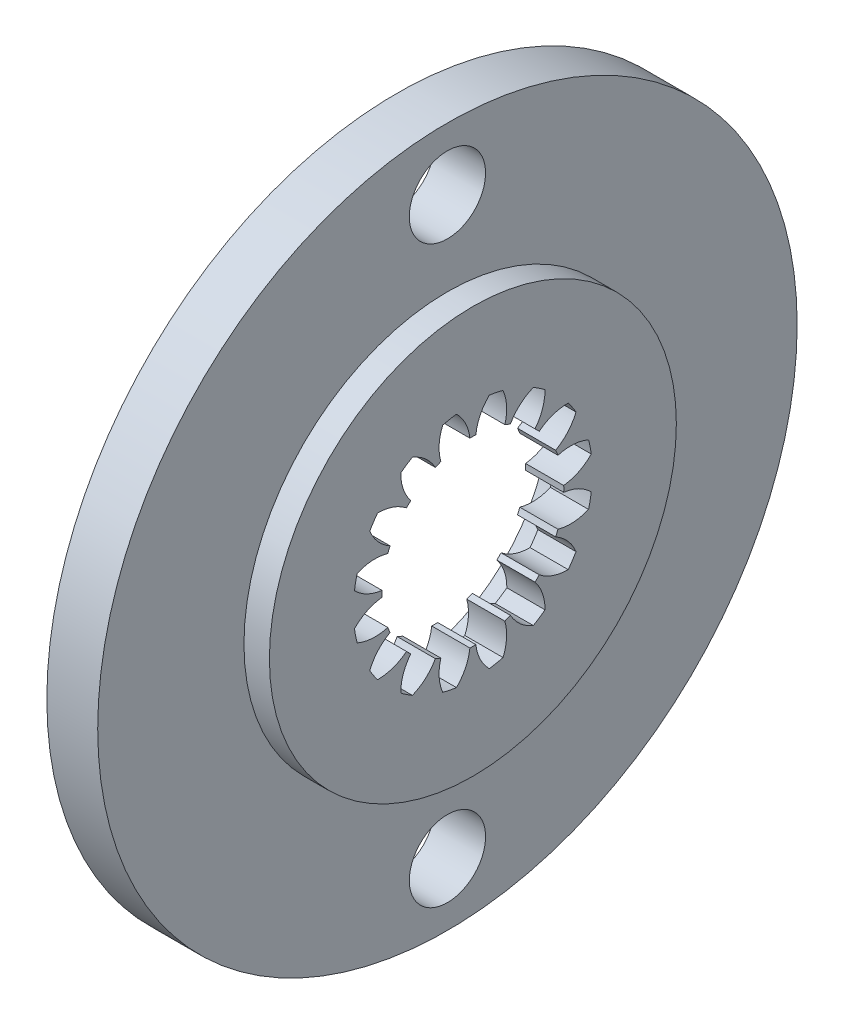
SolidWorks part; units mm, degrees
ref_plane "Plane1" through (0, 0, 0) normal (0, 0, 1) x (1, 0, 0)
ref_plane "Plane2" through (0, 0, 0) normal (0, 1, 0) x (1, 0, 0)
ref_plane "Plane3" through (0, 0, 0) normal (1, 0, 0) x (0, 0, -1)
sketch "HoldingSke" plane through (0, 0, 0) normal (0, 1, 0) x (1, 0, 0)
  line L0 (0, 0) -> (1.9225, -0.5513)
  line L1 (-15, 0) -> (100, 0) construction
  line L2 (0, 0) -> (-2.1039, 2.3779)
  line L3 (0, 0) -> (-11.863, 4.5341)
  line L4 (0, 0) -> (8.3015, 2.3804)
  line L5 (0, 0) -> (-46.8476, -17.4728)
  line L6 (0, 0) -> (-6.2172, -4.1948)
  line L7 (-2.1039, 2.3779) -> (8.6586, 51.2059)
  line L8 (-76.2, 54.61) -> (-75.3, 54.61)
  line L9 (-67.7845, 28.3722) -> (-49.3413, 33.142)
  line L10 (-76.2, 71.12) -> (104.1128, 71.12)
  line L11 (0, 0) -> (-7.5, 0)
  line L12 (-76.2, 101.6) -> (-76.181, 101.6)
  line L13 (24.9733, 27.94) -> (52.9518, 28.4284)
  line L14 (24.9733, 27.94) -> (24.9743, 27.94)
  line L15 (24.9733, 27.94) -> (100.4006, 29.5858)
  line L16 (-63.627, -0.5) -> (-12.827, -0.5)
  circle A0 centre (0, 0) radius 2.5
  circle A1 centre (0, 0) radius 3.374
  circle A2 centre (0, 0) radius 37.5
  circle A3 centre (0, 0) radius 2.5
  dimension "MHD" = 6.748
  dimension "Hub_dia" = 75
  dimension "Bore" = 5
  dimension "MBD" = 5
  dimension "Num_teeth" = 16
  dimension "Pitch" = 2
  dimension "Overall_len" = 50
  dimension "Show_teeth" = 16
  dimension "Thickness" = 7.5
  dimension "OAL" = 50.0001
  dimension "T_dim" = 0.9
  dimension "Ap" = 14.5
  dimension "H" = 19.05
  dimension "Pitch_radius" = 180.3128
  dimension "Width" = 7.5
  dimension "Backlash" = 0.019
  dimension "Addendum_fac" = 1
  dimension "Dedendum_fac" = 1.25
  dimension "Clearance_fac" = 0.25
  dimension "Dedendum_add" = 0.001
  dimension "Module" = 0.5
sketch "BasProSke" plane through (0, 0, 0) normal (0, 1, 0) x (1, 0, 0)
  line L0 (-10, 0) -> (60, 0) construction
  line L1 (0, 0) -> (0, 4.5)
  line L2 (0, 0) -> (7.5, 0)
  line L3 (7.5, 0) -> (7.5, 4.5)
  line L4 (7.5, 4.5) -> (0, 4.5)
  dimension "Thickness" = 7.5
  dimension "Diameter" = 9
revolve "Base-Revolve" add sketch "BasProSke" angle 360 about L0
sketch "TooCutSke" plane through (0, 0, 0) normal (1, 0, 0) x (0, 0, -1)
  line L1 (0, 0) -> (0, 107) construction
  line L2 (0, 0) -> (-0.4253, 3.9773) construction
  line L3 (0, 0) -> (-1.5544, 7.8146) construction
  line L4 (-0.4253, 3.9773) -> (-0.7772, 3.9073) construction
  arc A0 (0.306, 3.3601) -> (-0.306, 3.3601) centre (0, 0) ccw
  arc A1 (0.7382, 4.4648) -> (-0.7382, 4.4648) centre (0, 0) ccw
  circle A2 centre (0, 0) radius 4 construction
  circle A3 centre (0, 0) radius 3.8726 construction
  arc A4 (-0.306, 3.3601) -> (-0.7382, 4.4648) centre (-1.906, 3.3711) ccw
  arc A5 (0.7382, 4.4648) -> (0.306, 3.3601) centre (1.906, 3.3711) ccw
  dimension "Root_dia" = 6.748
  dimension "Overcut_dia" = 9.0508
  dimension "Pitch_dia" = 8
  dimension "Base_dia" = 7.7452
  dimension "Flank_rad" = 1.6
  dimension "Half_ang" = 11.25
  dimension "Half_CT" = 0.3588
extrude "ToothCut" cut sketch "TooCutSke" along normal through all
fillet "Breaks" [suppressed] radius 0.01
fillet "RootFillets" [suppressed] radius 0.126
pattern_circular "TeethCuts" count 16 every 22.5 about axis through (-10, 0, 0) along (1, 0, 0) of "ToothCut", "RootFillets", "Breaks"
sketch "HubNeaOneSke" plane through (0, 0, 0) normal (-1, 0, 0) x (0, 0, 1)
  circle A0 centre (0, 0) radius 3.374
  dimension "Diameter" = 6.748
extrude "HubNearOne" [suppressed] add sketch "HubNeaOneSke" along normal blind 42.5001
sketch "HubNeaBotSke" plane through (0, 0, 0) normal (-1, 0, 0) x (0, 0, 1)
  circle A0 centre (0, 0) radius 3.374
  dimension "Diameter" = 6.748
extrude "HubNearBoth" [suppressed] add sketch "HubNeaBotSke" along normal blind 21.25
ref_plane "FarPln" through (7.5, 0, 0) normal (1, 0, 0) x (0, 0, -1)
sketch "HubFarSke" plane through (7.5, 0, 0) normal (1, 0, 0) x (0, 0, -1)
  circle A0 centre (0, 0) radius 3.374
  dimension "Diameter" = 6.748
extrude "HubFar" [suppressed] add sketch "HubFarSke" along normal blind 21.25
sketch "BorSke" plane through (0, 0, 0) normal (1, 0, 0) x (0, 0, -1)
  circle A0 centre (0, 0) radius 2.5
  dimension "Diameter" = 5
extrude "Bore" cut sketch "BorSke" along normal mid plane 100.0001
sketch "KeySke" plane through (0, 0, 0) normal (1, 0, 0) x (0, 0, -1)
  line L0 (-1, 0) -> (-1, 3.4)
  line L1 (-1, 3.4) -> (1, 3.4)
  line L2 (1, 3.4) -> (1, 0)
  line L3 (0, 0) -> (0, 34) construction
  line L4 (-1, 0) -> (1, 0)
  dimension "Offset" = 3.4
  dimension "Width" = 2
extrude "Keyway" [suppressed] cut sketch "KeySke" along normal mid plane 100.0001
pattern_circular "Keyway2" [suppressed] count 2 every 90 about axis through (-10, 0, 0) along (1, 0, 0)
sketch "Esquisse4" plane through (0, 0, 0) normal (-1, 0, 0) x (0, 0, 1)
  circle A1 centre (0, 0) radius 6
  dimension "D1" = 12
extrude "Boss.-Extru.3" add sketch "Esquisse4" along normal blind 1
sketch "Esquisse5" plane through (7.5, 0, 0) normal (1, 0, 0) x (0, 0, -1)
  circle A0 centre (0, 0) radius 2.85
  circle A1 centre (0, 0) radius 6.0278
extrude "Boss.-Extru.4" add sketch "Esquisse5" along normal blind 1
sketch "Esquisse7" plane through (0, 0, 0) normal (1, 0, 0) x (0, 0, -1)
  circle A0 centre (0, 0) radius 3.0071
extrude "Boss.-Extru.6" add sketch "Esquisse7" along normal up to surface (8.5 mm away) up to face at (8.5, 0, -6.0278)
sketch "Esquisse9" plane through (-1, 0, 0) normal (-1, 0, 0) x (0, 0, 1)
  circle A0 centre (0, 0) radius 13.75
  circle A1 centre (0, 0) radius 5.5
  dimension "D1" = 27.5
  dimension "D2" = 11
extrude "Boss.-Extru.8" add sketch "Esquisse9" along normal blind 2
sketch "Esquisse10" plane through (-3, 0, 0) normal (-1, 0, 0) x (0, 0, 1)
  line L0 (-13.75, 0) -> (13.75, 0) construction
  line L1 (0, 13.75) -> (0, -13.75) construction
  circle A0 centre (0, 11.3) radius 1.5
  circle A1 centre (0, -11.3) radius 1.5
  circle A2 centre (0, 0) radius 13.75 construction
  dimension "D1" = 0
  dimension "D2" = 3
  dimension "D3" = 11.3
  dimension "D4" = 3
  dimension "D5" = 11.3
  dimension "D6" = 0
extrude "Enlèv. mat.-Extru.3" cut sketch "Esquisse10" against normal through all
sketch "Esquisse11" plane through (-1, 0, 0) normal (-1, 0, 0) x (0, 0, 1)
  circle A0 centre (0, 0) radius 3
  dimension "D1" = 6
extrude "Enlèv. mat.-Extru.4" cut sketch "Esquisse11" against normal blind 4
sketch "Esquisse12" plane through (3, 0, 0) normal (-1, 0, 0) x (0, 0, 1)
  circle A0 centre (0, 0) radius 3
extrude "Boss.-Extru.9" add sketch "Esquisse12" along normal up to surface (4 mm away) up to face at (-1, 0, 3)
sketch "Esquisse13" plane through (-1, 0, 0) normal (-1, 0, 0) x (0, 0, 1)
  circle A0 centre (0, 0) radius 5.5
extrude "Boss.-Extru.10" add sketch "Esquisse13" along normal up to surface (2 mm away) up to face at (-3, 11.3, 1.5)
sketch "Esquisse16" plane through (-1, 0, 0) normal (1, 0, 0) x (0, 0, -1)
  circle A0 centre (0, 0) radius 8
  dimension "D1" = 16
extrude "Boss.-Extru.11" add sketch "Esquisse16" along normal up to surface (1 mm away) up to face at (0, 0, 6)
sketch "Esquisse14" plane through (-3, 0, 0) normal (-1, 0, 0) x (0, 0, 1)
  circle A0 centre (0, 0) radius 6
  dimension "D1" = 12
extrude "Enlèv. mat.-Extru.5" cut sketch "Esquisse14" against normal blind 1.5
sketch "Esquisse15" plane through (-1.5, 0, 0) normal (-1, 0, 0) x (0, 0, 1)
  circle A0 centre (0, 0) radius 3.25
  dimension "D1" = 6.5
extrude "Enlèv. mat.-Extru.6" cut sketch "Esquisse15" against normal blind 4.5
sketch "Esquisse17" plane through (8.5, 0, 0) normal (1, 0, 0) x (0, 0, -1)
  circle A0 centre (0, 0) radius 6.0278
extrude "Enlèv. mat.-Extru.7" cut sketch "Esquisse17" against normal blind 4
sketch "Esquisse18" plane through (4.5, 0, 0) normal (1, 0, 0) x (0, 0, -1)
  arc A128 (3.5721, 0.1172) -> (4.6555, 0.645) centre (3.3711, 1.906) ccw
  arc A129 (4.6555, 0.645) -> (4.548, 1.1857) centre (0, 0) ccw
  arc A130 (4.548, 1.1857) -> (3.345, 1.2587) centre (3.8439, -0.4708) ccw
  arc A131 (3.345, 1.2587) -> (3.2553, 1.4753) centre (0, 0) ccw
  arc A132 (3.2553, 1.4753) -> (4.0543, 2.3775) centre (2.3851, 3.051) ccw
  arc A133 (4.0543, 2.3775) -> (3.748, 2.8359) centre (0, 0) ccw
  arc A134 (3.748, 2.8359) -> (2.6087, 2.4429) centre (3.7314, 1.036) ccw
  arc A135 (2.6087, 2.4429) -> (2.4429, 2.6087) centre (0, 0) ccw
  arc A136 (2.4429, 2.6087) -> (2.8359, 3.748) centre (1.036, 3.7314) ccw
  arc A137 (2.8359, 3.748) -> (2.3775, 4.0543) centre (0, 0) ccw
  arc A138 (2.3775, 4.0543) -> (1.4753, 3.2553) centre (3.051, 2.3851) ccw
  arc A139 (1.4753, 3.2553) -> (1.2587, 3.345) centre (0, 0) ccw
  arc A140 (1.2587, 3.345) -> (1.1857, 4.548) centre (-0.4708, 3.8439) ccw
  arc A141 (1.1857, 4.548) -> (0.645, 4.6555) centre (0, 0) ccw
  arc A142 (0.645, 4.6555) -> (0.1172, 3.5721) centre (1.906, 3.3711) ccw
  arc A143 (0.1172, 3.5721) -> (-0.1172, 3.5721) centre (0, 0) ccw
  arc A144 (-0.1172, 3.5721) -> (-0.645, 4.6555) centre (-1.906, 3.3711) ccw
  arc A145 (-0.645, 4.6555) -> (-1.1857, 4.548) centre (0, 0) ccw
  arc A146 (-1.1857, 4.548) -> (-1.2587, 3.345) centre (0.4708, 3.8439) ccw
  arc A147 (-1.2587, 3.345) -> (-1.4753, 3.2553) centre (0, 0) ccw
  arc A148 (-1.4753, 3.2553) -> (-2.3775, 4.0543) centre (-3.051, 2.3851) ccw
  arc A149 (-2.3775, 4.0543) -> (-2.8359, 3.748) centre (0, 0) ccw
  arc A150 (-2.8359, 3.748) -> (-2.4429, 2.6087) centre (-1.036, 3.7314) ccw
  arc A151 (-2.4429, 2.6087) -> (-2.6087, 2.4429) centre (0, 0) ccw
  arc A152 (-2.6087, 2.4429) -> (-3.748, 2.8359) centre (-3.7314, 1.036) ccw
  arc A153 (-3.748, 2.8359) -> (-4.0543, 2.3775) centre (0, 0) ccw
  arc A154 (-4.0543, 2.3775) -> (-3.2553, 1.4753) centre (-2.3851, 3.051) ccw
  arc A155 (-3.2553, 1.4753) -> (-3.345, 1.2587) centre (0, 0) ccw
  arc A156 (-3.345, 1.2587) -> (-4.548, 1.1857) centre (-3.8439, -0.4708) ccw
  arc A157 (-4.548, 1.1857) -> (-4.6555, 0.645) centre (0, 0) ccw
  arc A158 (-4.6555, 0.645) -> (-3.5721, 0.1172) centre (-3.3711, 1.906) ccw
  arc A159 (-3.5721, 0.1172) -> (-3.5721, -0.1172) centre (0, 0) ccw
  arc A160 (-3.5721, -0.1172) -> (-4.6555, -0.645) centre (-3.3711, -1.906) ccw
  arc A161 (-4.6555, -0.645) -> (-4.548, -1.1857) centre (0, 0) ccw
  arc A162 (-4.548, -1.1857) -> (-3.345, -1.2587) centre (-3.8439, 0.4708) ccw
  arc A163 (-3.345, -1.2587) -> (-3.2553, -1.4753) centre (0, 0) ccw
  arc A164 (-3.2553, -1.4753) -> (-4.0543, -2.3775) centre (-2.3851, -3.051) ccw
  arc A165 (-4.0543, -2.3775) -> (-3.748, -2.8359) centre (0, 0) ccw
  arc A166 (-3.748, -2.8359) -> (-2.6087, -2.4429) centre (-3.7314, -1.036) ccw
  arc A167 (-2.6087, -2.4429) -> (-2.4429, -2.6087) centre (0, 0) ccw
  arc A168 (-2.4429, -2.6087) -> (-2.8359, -3.748) centre (-1.036, -3.7314) ccw
  arc A169 (-2.8359, -3.748) -> (-2.3775, -4.0543) centre (0, 0) ccw
  arc A170 (-2.3775, -4.0543) -> (-1.4753, -3.2553) centre (-3.051, -2.3851) ccw
  arc A171 (-1.4753, -3.2553) -> (-1.2587, -3.345) centre (0, 0) ccw
  arc A172 (-1.2587, -3.345) -> (-1.1857, -4.548) centre (0.4708, -3.8439) ccw
  arc A173 (-1.1857, -4.548) -> (-0.645, -4.6555) centre (0, 0) ccw
  arc A174 (-0.645, -4.6555) -> (-0.1172, -3.5721) centre (-1.906, -3.3711) ccw
  arc A175 (-0.1172, -3.5721) -> (0.1172, -3.5721) centre (0, 0) ccw
  arc A176 (0.1172, -3.5721) -> (0.645, -4.6555) centre (1.906, -3.3711) ccw
  arc A177 (0.645, -4.6555) -> (1.1857, -4.548) centre (0, 0) ccw
  arc A178 (1.1857, -4.548) -> (1.2587, -3.345) centre (-0.4708, -3.8439) ccw
  arc A179 (1.2587, -3.345) -> (1.4753, -3.2553) centre (0, 0) ccw
  arc A180 (1.4753, -3.2553) -> (2.3775, -4.0543) centre (3.051, -2.3851) ccw
  arc A181 (2.3775, -4.0543) -> (2.8359, -3.748) centre (0, 0) ccw
  arc A182 (2.8359, -3.748) -> (2.4429, -2.6087) centre (1.036, -3.7314) ccw
  arc A183 (2.4429, -2.6087) -> (2.6087, -2.4429) centre (0, 0) ccw
  arc A184 (2.6087, -2.4429) -> (3.748, -2.8359) centre (3.7314, -1.036) ccw
  arc A185 (3.748, -2.8359) -> (4.0543, -2.3775) centre (0, 0) ccw
  arc A186 (4.0543, -2.3775) -> (3.2553, -1.4753) centre (2.3851, -3.051) ccw
  arc A187 (3.2553, -1.4753) -> (3.345, -1.2587) centre (0, 0) ccw
  arc A188 (3.345, -1.2587) -> (4.548, -1.1857) centre (3.8439, 0.4708) ccw
  arc A189 (4.548, -1.1857) -> (4.6555, -0.645) centre (0, 0) ccw
  arc A190 (4.6555, -0.645) -> (3.5721, -0.1172) centre (3.3711, -1.906) ccw
  arc A191 (3.5721, -0.1172) -> (3.5721, 0.1172) centre (0, 0) ccw
  arc A256 (3.5721, 0.1172) -> (4.6555, 0.645) centre (3.3711, 1.906) ccw
  arc A257 (4.6555, 0.645) -> (4.548, 1.1857) centre (0, 0) ccw
  arc A258 (4.548, 1.1857) -> (3.345, 1.2587) centre (3.8439, -0.4708) ccw
  arc A259 (3.345, 1.2587) -> (3.2553, 1.4753) centre (0, 0) ccw
  arc A260 (3.2553, 1.4753) -> (4.0543, 2.3775) centre (2.3851, 3.051) ccw
  arc A261 (4.0543, 2.3775) -> (3.748, 2.8359) centre (0, 0) ccw
  arc A262 (3.748, 2.8359) -> (2.6087, 2.4429) centre (3.7314, 1.036) ccw
  arc A263 (2.6087, 2.4429) -> (2.4429, 2.6087) centre (0, 0) ccw
  arc A264 (2.4429, 2.6087) -> (2.8359, 3.748) centre (1.036, 3.7314) ccw
  arc A265 (2.8359, 3.748) -> (2.3775, 4.0543) centre (0, 0) ccw
  arc A266 (2.3775, 4.0543) -> (1.4753, 3.2553) centre (3.051, 2.3851) ccw
  arc A267 (1.4753, 3.2553) -> (1.2587, 3.345) centre (0, 0) ccw
  arc A268 (1.2587, 3.345) -> (1.1857, 4.548) centre (-0.4708, 3.8439) ccw
  arc A269 (1.1857, 4.548) -> (0.645, 4.6555) centre (0, 0) ccw
  arc A270 (0.645, 4.6555) -> (0.1172, 3.5721) centre (1.906, 3.3711) ccw
  arc A271 (0.1172, 3.5721) -> (-0.1172, 3.5721) centre (0, 0) ccw
  arc A272 (-0.1172, 3.5721) -> (-0.645, 4.6555) centre (-1.906, 3.3711) ccw
  arc A273 (-0.645, 4.6555) -> (-1.1857, 4.548) centre (0, 0) ccw
  arc A274 (-1.1857, 4.548) -> (-1.2587, 3.345) centre (0.4708, 3.8439) ccw
  arc A275 (-1.2587, 3.345) -> (-1.4753, 3.2553) centre (0, 0) ccw
  arc A276 (-1.4753, 3.2553) -> (-2.3775, 4.0543) centre (-3.051, 2.3851) ccw
  arc A277 (-2.3775, 4.0543) -> (-2.8359, 3.748) centre (0, 0) ccw
  arc A278 (-2.8359, 3.748) -> (-2.4429, 2.6087) centre (-1.036, 3.7314) ccw
  arc A279 (-2.4429, 2.6087) -> (-2.6087, 2.4429) centre (0, 0) ccw
  arc A280 (-2.6087, 2.4429) -> (-3.748, 2.8359) centre (-3.7314, 1.036) ccw
  arc A281 (-3.748, 2.8359) -> (-4.0543, 2.3775) centre (0, 0) ccw
  arc A282 (-4.0543, 2.3775) -> (-3.2553, 1.4753) centre (-2.3851, 3.051) ccw
  arc A283 (-3.2553, 1.4753) -> (-3.345, 1.2587) centre (0, 0) ccw
  arc A284 (-3.345, 1.2587) -> (-4.548, 1.1857) centre (-3.8439, -0.4708) ccw
  arc A285 (-4.548, 1.1857) -> (-4.6555, 0.645) centre (0, 0) ccw
  arc A286 (-4.6555, 0.645) -> (-3.5721, 0.1172) centre (-3.3711, 1.906) ccw
  arc A287 (-3.5721, 0.1172) -> (-3.5721, -0.1172) centre (0, 0) ccw
  arc A288 (-3.5721, -0.1172) -> (-4.6555, -0.645) centre (-3.3711, -1.906) ccw
  arc A289 (-4.6555, -0.645) -> (-4.548, -1.1857) centre (0, 0) ccw
  arc A290 (-4.548, -1.1857) -> (-3.345, -1.2587) centre (-3.8439, 0.4708) ccw
  arc A291 (-3.345, -1.2587) -> (-3.2553, -1.4753) centre (0, 0) ccw
  arc A292 (-3.2553, -1.4753) -> (-4.0543, -2.3775) centre (-2.3851, -3.051) ccw
  arc A293 (-4.0543, -2.3775) -> (-3.748, -2.8359) centre (0, 0) ccw
  arc A294 (-3.748, -2.8359) -> (-2.6087, -2.4429) centre (-3.7314, -1.036) ccw
  arc A295 (-2.6087, -2.4429) -> (-2.4429, -2.6087) centre (0, 0) ccw
  arc A296 (-2.4429, -2.6087) -> (-2.8359, -3.748) centre (-1.036, -3.7314) ccw
  arc A297 (-2.8359, -3.748) -> (-2.3775, -4.0543) centre (0, 0) ccw
  arc A298 (-2.3775, -4.0543) -> (-1.4753, -3.2553) centre (-3.051, -2.3851) ccw
  arc A299 (-1.4753, -3.2553) -> (-1.2587, -3.345) centre (0, 0) ccw
  arc A300 (-1.2587, -3.345) -> (-1.1857, -4.548) centre (0.4708, -3.8439) ccw
  arc A301 (-1.1857, -4.548) -> (-0.645, -4.6555) centre (0, 0) ccw
  arc A302 (-0.645, -4.6555) -> (-0.1172, -3.5721) centre (-1.906, -3.3711) ccw
  arc A303 (-0.1172, -3.5721) -> (0.1172, -3.5721) centre (0, 0) ccw
  arc A304 (0.1172, -3.5721) -> (0.645, -4.6555) centre (1.906, -3.3711) ccw
  arc A305 (0.645, -4.6555) -> (1.1857, -4.548) centre (0, 0) ccw
  arc A306 (1.1857, -4.548) -> (1.2587, -3.345) centre (-0.4708, -3.8439) ccw
  arc A307 (1.2587, -3.345) -> (1.4753, -3.2553) centre (0, 0) ccw
  arc A308 (1.4753, -3.2553) -> (2.3775, -4.0543) centre (3.051, -2.3851) ccw
  arc A309 (2.3775, -4.0543) -> (2.8359, -3.748) centre (0, 0) ccw
  arc A310 (2.8359, -3.748) -> (2.4429, -2.6087) centre (1.036, -3.7314) ccw
  arc A311 (2.4429, -2.6087) -> (2.6087, -2.4429) centre (0, 0) ccw
  arc A312 (2.6087, -2.4429) -> (3.748, -2.8359) centre (3.7314, -1.036) ccw
  arc A313 (3.748, -2.8359) -> (4.0543, -2.3775) centre (0, 0) ccw
  arc A314 (4.0543, -2.3775) -> (3.2553, -1.4753) centre (2.3851, -3.051) ccw
  arc A315 (3.2553, -1.4753) -> (3.345, -1.2587) centre (0, 0) ccw
  arc A316 (3.345, -1.2587) -> (4.548, -1.1857) centre (3.8439, 0.4708) ccw
  arc A317 (4.548, -1.1857) -> (4.6555, -0.645) centre (0, 0) ccw
  arc A318 (4.6555, -0.645) -> (3.5721, -0.1172) centre (3.3711, -1.906) ccw
  arc A319 (3.5721, -0.1172) -> (3.5721, 0.1172) centre (0, 0) ccw
  dimension "D1" = 0.2
extrude "Enlèv. mat.-Extru.8" cut sketch "Esquisse18" against normal up to surface (6 mm away) up to face at (-1.5, 0, 3.25)
equation "' \"Module@HoldingSke\" = 6.35"
equation "' \"Num_teeth@HoldingSke\" = 12"
equation "' \"Ap@HoldingSke\" =  20"
equation "' \"Ap@HoldingSke\" = 20"
equation "' \"Width@HoldingSke\" = 0.5 * 25.4"
equation "' \"Hub_dia@HoldingSke\"= 1 * 25.4"
equation "' \"Hub_dia@HoldingSke\" = 1 * 25.4"
equation "' \"Overall_len@HoldingSke\" = 1.0 * 25.4"
equation "' \"Bore@HoldingSke\" = 0.75 * 25.4"
equation "' \"T_dim@HoldingSke\" = 0.1 * 25.4"
equation "' \"Width@KeySke\" = 0.25 * 25.4"
equation "' \"Show_teeth@HoldingSke\" = 13"
equation "' \"Backlash@HoldingSke\" = 0.009 * 25.4"
equation "' \"Addendum_fac@HoldingSke\" = 1.0"
equation "' \"Dedendum_fac@HoldingSke\" = 1.25"
equation "' \"Dedendum_add@HoldingSke\" = 0.00005 * 25.4"
equation "' \"Clearance_fac@HoldingSke\" = 0.25"
equation "\"Pitch@HoldingSke\" = 1 / \"Module@HoldingSke\""
equation "\"Overcut_dia@TooCutSke\" = (\"Num_teeth@HoldingSke\" + 2 * \"Addendum_fac@HoldingSke\") / \"Pitch@HoldingSke\" + 0.002 * 25.4"
equation "\"Pitch_dia@TooCutSke\" = \"Num_teeth@HoldingSke\" / \"Pitch@HoldingSke\""
equation "\"Base_dia@TooCutSke\" = \"Num_teeth@HoldingSke\" / \"Pitch@HoldingSke\" * cos((\"Ap@HoldingSke\"  * 3.14159265 / 180))"
equation "\"Root_dia@TooCutSke\" = (\"Num_teeth@HoldingSke\" + 2) / \"Pitch@HoldingSke\" - 2 * (\"Addendum_fac@HoldingSke\" + \"Dedendum_fac@HoldingSke\") / \"Pitch@HoldingSke\" - \"Dedendum_add@HoldingSke\" * 2"
equation "\"Half_ang@TooCutSke\" = 180 / \"Num_teeth@HoldingSke\""
equation "\"Half_CT@TooCutSke\" = \"Num_teeth@HoldingSke\" / \"Pitch@HoldingSke\" * sin((3.14159265 / 2 / \"Num_teeth@HoldingSke\")) / 2 - 7 * \"Backlash@HoldingSke\" / 4"
equation "\"Flank_rad@TooCutSke\" = \"Num_teeth@HoldingSke\" / \"Pitch@HoldingSke\" / 5"
equation "\"Radius@RootFillets\" = \"Clearance_fac@HoldingSke\" / \"Pitch@HoldingSke\" + \"Dedendum_add@HoldingSke\""
equation "\"Break_rad@Breaks\" = 0.02 / \"Pitch@HoldingSke\""
equation "\"Thickness@HoldingSke\" = \"Width@HoldingSke\""
equation "\"OAL@HoldingSke\" = \"Thickness@HoldingSke\""
equation "\"MHD@HoldingSke\" = (\"Num_teeth@HoldingSke\" + 2) / \"Pitch@HoldingSke\" - 2 * (\"Addendum_fac@HoldingSke\" + \"Dedendum_fac@HoldingSke\")  / \"Pitch@HoldingSke\" - \"Dedendum_add@HoldingSke\" * 2"
equation "\"MBD@HoldingSke\" = (\"Num_teeth@HoldingSke\" + 2) / \"Pitch@HoldingSke\" - 2 * (\"Addendum_fac@HoldingSke\" + \"Dedendum_fac@HoldingSke\")  / \"Pitch@HoldingSke\" - \"Dedendum_add@HoldingSke\" * 2 - 0.002 * 25.4"
equation "\"MHD@HoldingSke\" = ((sgn( \"MHD@HoldingSke\" - \"Hub_dia@HoldingSke\" )-1)*( \"MHD@HoldingSke\" - \"Hub_dia@HoldingSke\" ))/-2+ \"Hub_dia@HoldingSke\""
equation "\"MBD@HoldingSke\" = ((sgn( \"MBD@HoldingSke\" - \"Bore@HoldingSke\" )-1)*( \"MBD@HoldingSke\" - \"Bore@HoldingSke\" ))/-2+ \"Bore@HoldingSke\""
equation "\"OAL@HoldingSke\" = ((sgn( \"OAL@HoldingSke\" - \"Overall_len@HoldingSke\" )+1)*( \"OAL@HoldingSke\" - \"Overall_len@HoldingSke\" ))/2 + \"Overall_len@HoldingSke\" + 0.000002 * 25.4"
equation "\"Num_teeth@TeethCuts\" = int( \"Show_teeth@HoldingSke\" ) + 1"
equation "\"Num_teeth@TeethCuts\" = ((sgn( \"Num_teeth@TeethCuts\" - \"Num_teeth@HoldingSke\" )-1)*( \"Num_teeth@TeethCuts\" - \"Num_teeth@HoldingSke\" ))/-2+ \"Num_teeth@HoldingSke\""
equation "\"Num_teeth@TeethCuts\" = ((sgn( \"Num_teeth@TeethCuts\" - 2.0)+1)*( \"Num_teeth@TeethCuts\" - 2.0))/2 +2.0"
equation "\"Angle@TeethCuts\" = 360.0 / \"Num_teeth@HoldingSke\""
equation "\"Diameter@BasProSke\" = (\"Num_teeth@HoldingSke\" + 2 * \"Addendum_fac@HoldingSke\") / \"Pitch@HoldingSke\""
equation "\"Thickness@BasProSke\"  = \"Thickness@HoldingSke\""
equation "' \"Fillet_rad@BasProSke\" =  \"Thickness@HoldingSke\" * 0.05"
equation "' \"Fillet_rad@BasProSke\" = \"Thickness@HoldingSke\" * 0.05"
equation "\"MHD@HoldingSke\" = ((sgn( \"MHD@HoldingSke\" - \"Root_dia@TooCutSke\" )-1)*( \"MHD@HoldingSke\" - \"Root_dia@TooCutSke\" ))/-2+ \"Root_dia@TooCutSke\""
equation "\"Diameter@HubNeaOneSke\" = \"MHD@HoldingSke\""
equation "\"Length@HubNearOne\" = \"OAL@HoldingSke\" - \"Thickness@BasProSke\""
equation "\"Diameter@HubNeaBotSke\" = \"MHD@HoldingSke\""
equation "\"Length@HubNearBoth\" = ( \"OAL@HoldingSke\" - \"Thickness@BasProSke\" ) / 2.0"
equation "\"Thickness@FarPln\" = \"Thickness@BasProSke\""
equation "\"Diameter@HubFarSke\" = \"MHD@HoldingSke\""
equation "\"Length@HubFar\" = ( \"OAL@HoldingSke\" - \"Thickness@BasProSke\" ) / 2.0"
equation "\"Diameter@BorSke\" = \"MBD@HoldingSke\""
equation "\"D1@Bore\" = \"OAL@HoldingSke\" * 2.0"
equation "\"D1@Keyway\" = \"OAL@HoldingSke\" * 2.0"
equation "\"Offset@KeySke\" = \"T_dim@HoldingSke\" + \"MBD@HoldingSke\" / 2.0"
